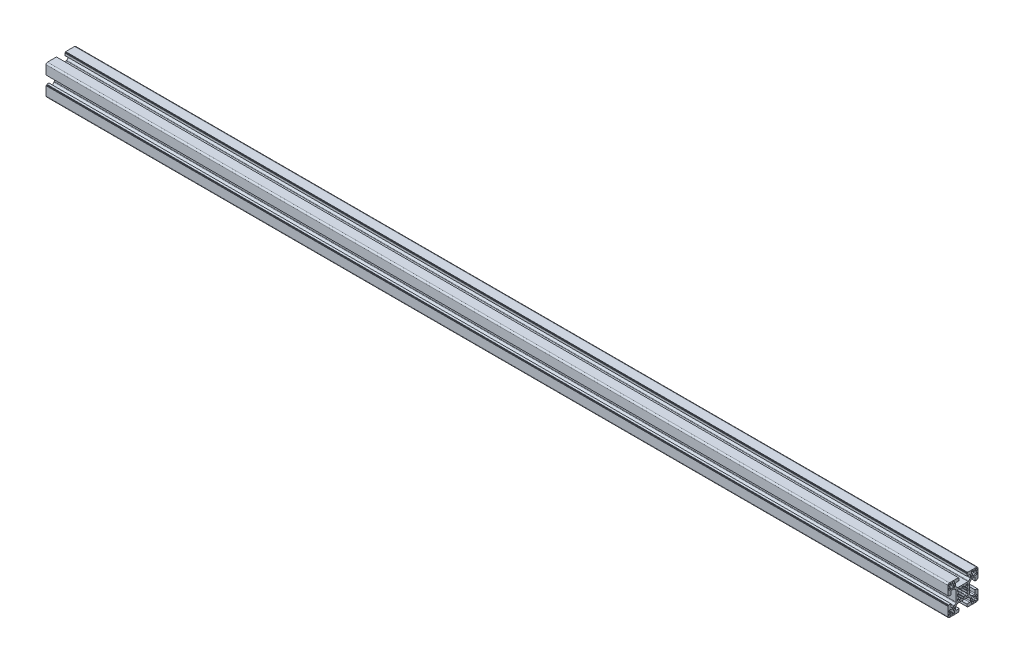
SolidWorks part; units mm, degrees
material "6061 Alloy"
ref_plane "Front Plane" through (0, 0, 0) normal (0, 0, 1) x (1, 0, 0)
ref_plane "Top Plane" through (0, 0, 0) normal (0, 1, 0) x (1, 0, 0)
ref_plane "Right Plane" through (0, 0, 0) normal (1, 0, 0) x (0, 0, -1)
sketch3d "3DSketch1"
  line L12 (-1068.9493, 47.0087, 0) -> (131.0507, 47.0087, 0)
  dimension "D1" = 1200
other " C:\\PROGRAM FILES\\SOLIDWORKS CORP\\SOLIDWORKS\\DATA\\WELDMENT PROFILES\\CUSTOM\\CUSTOM ROHR\\ALUPROFILE 40X40 - IS MISSING(1)"
ref_plane "Plane4" through (-1068.9493, 47.0087, 0) normal (1, 0, 0) x (0, 0, -1)
sketch "Sketch1" plane through (-1068.9493, 47.0087, 0) normal (1, 0, 0) x (0, 0, -1)
  line L0 (-20, 18) -> (-20, 6.1)
  line L1 (-20, 6.1) -> (-19, 6.1)
  line L2 (-19, 6.1) -> (-19, 5.1)
  line L3 (-19, 5.1) -> (-16, 5.1)
  line L4 (-16, 5.1) -> (-16, 9)
  line L5 (-15, 10) -> (-12.182, 10)
  line L6 (-11.4749, 9.7071) -> (-9.2929, 7.5251)
  line L7 (-9, 6.818) -> (-9, -6.818)
  line L8 (-9.2929, -7.5251) -> (-11.4749, -9.7071)
  line L9 (-12.182, -10) -> (-15, -10)
  line L10 (-16, -9) -> (-16, -5.1)
  line L11 (-16, -5.1) -> (-19, -5.1)
  line L12 (-19, -5.1) -> (-19, -6.1)
  line L13 (-19, -6.1) -> (-20, -6.1)
  line L14 (-20, -6.1) -> (-20, -18)
  line L15 (-18, -20) -> (-6.1, -20)
  line L16 (-6.1, -20) -> (-6.1, -19)
  line L17 (-6.1, -19) -> (-5.1, -19)
  line L18 (-5.1, -19) -> (-5.1, -16)
  line L19 (-5.1, -16) -> (-9, -16)
  line L20 (-10, -15) -> (-10, -12.182)
  line L21 (-9.7071, -11.4749) -> (-7.5251, -9.2929)
  line L22 (-6.818, -9) -> (6.818, -9)
  line L23 (7.5251, -9.2929) -> (9.7071, -11.4749)
  line L24 (10, -12.182) -> (10, -15)
  line L25 (9, -16) -> (5.1, -16)
  line L26 (5.1, -16) -> (5.1, -19)
  line L27 (5.1, -19) -> (6.1, -19)
  line L28 (6.1, -19) -> (6.1, -20)
  line L29 (6.1, -20) -> (18, -20)
  line L30 (20, -18) -> (20, -6.1)
  line L31 (20, -6.1) -> (19, -6.1)
  line L32 (19, -6.1) -> (19, -5.1)
  line L33 (19, -5.1) -> (16, -5.1)
  line L34 (16, -5.1) -> (16, -9)
  line L35 (15, -10) -> (12.182, -10)
  line L36 (11.4749, -9.7071) -> (9.2929, -7.5251)
  line L37 (9, -6.818) -> (9, 6.818)
  line L38 (9.2929, 7.5251) -> (11.4749, 9.7071)
  line L39 (12.182, 10) -> (15, 10)
  line L40 (16, 9) -> (16, 5.1)
  line L41 (16, 5.1) -> (19, 5.1)
  line L42 (19, 5.1) -> (19, 6.1)
  line L43 (19, 6.1) -> (20, 6.1)
  line L44 (20, 6.1) -> (20, 18)
  line L45 (18, 20) -> (6.1, 20)
  line L46 (6.1, 20) -> (6.1, 19)
  line L47 (6.1, 19) -> (5.1, 19)
  line L48 (5.1, 19) -> (5.1, 16)
  line L49 (5.1, 16) -> (9, 16)
  line L50 (10, 15) -> (10, 12.182)
  line L51 (9.7071, 11.4749) -> (7.5251, 9.2929)
  line L52 (6.818, 9) -> (-6.818, 9)
  line L53 (-7.5251, 9.2929) -> (-9.7071, 11.4749)
  line L54 (-10, 12.182) -> (-10, 15)
  line L55 (-9, 16) -> (-5.1, 16)
  line L56 (-5.1, 16) -> (-5.1, 19)
  line L57 (-5.1, 19) -> (-6.1, 19)
  line L58 (-6.1, 19) -> (-6.1, 20)
  line L59 (-6.1, 20) -> (-18, 20)
  line L60 (-15.8, 18.5) -> (-15.8, 16.8697)
  line L61 (-15.8, 16.8697) -> (-14.2, 16.8697)
  line L62 (-14.2, 16.8697) -> (-14.2, 18.5)
  line L63 (-14.2, 18.5) -> (-11.5, 18.5)
  line L64 (-11.5, 18.5) -> (-11.5, 15.1697)
  line L65 (-11.5, 15.1697) -> (-12.5, 15.1697)
  line L66 (-12.5, 15.1697) -> (-12.5, 13.5697)
  line L67 (-12.5, 13.5697) -> (-11.5, 13.5697)
  line L68 (-11.5, 13.5697) -> (-11.5, 11.5)
  line L69 (-11.5, 11.5) -> (-14.2, 11.5)
  line L70 (-14.2, 11.5) -> (-14.2, 12.5)
  line L71 (-14.2, 12.5) -> (-15.8, 12.5)
  line L72 (-15.8, 12.5) -> (-15.8, 11.5)
  line L73 (-15.8, 11.5) -> (-18.5, 11.5)
  line L74 (-18.5, 11.5) -> (-18.5, 14.2)
  line L75 (-18.5, 14.2) -> (-17.5, 14.2)
  line L76 (-17.5, 14.2) -> (-17.5, 15.8)
  line L77 (-17.5, 15.8) -> (-18.5, 15.8)
  line L78 (-18.5, 15.8) -> (-18.5, 17.5)
  line L79 (-17.5, 18.5) -> (-15.8, 18.5)
  line L80 (0, 9) -> (0, -9) construction
  line L81 (-9, 0) -> (9, 0) construction
  line L82 (17.5, 18.5) -> (15.8, 18.5)
  line L83 (18.5, 15.8) -> (18.5, 17.5)
  line L84 (17.5, 15.8) -> (18.5, 15.8)
  line L85 (17.5, 14.2) -> (17.5, 15.8)
  line L86 (18.5, 14.2) -> (17.5, 14.2)
  line L87 (18.5, 11.5) -> (18.5, 14.2)
  line L88 (15.8, 11.5) -> (18.5, 11.5)
  line L89 (15.8, 12.5) -> (15.8, 11.5)
  line L90 (14.2, 12.5) -> (15.8, 12.5)
  line L91 (14.2, 11.5) -> (14.2, 12.5)
  line L92 (11.5, 11.5) -> (14.2, 11.5)
  line L93 (11.5, 13.5697) -> (11.5, 11.5)
  line L94 (12.5, 13.5697) -> (11.5, 13.5697)
  line L95 (12.5, 15.1697) -> (12.5, 13.5697)
  line L96 (11.5, 15.1697) -> (12.5, 15.1697)
  line L97 (11.5, 18.5) -> (11.5, 15.1697)
  line L98 (14.2, 18.5) -> (11.5, 18.5)
  line L99 (14.2, 16.8697) -> (14.2, 18.5)
  line L100 (15.8, 16.8697) -> (14.2, 16.8697)
  line L101 (15.8, 18.5) -> (15.8, 16.8697)
  line L102 (15.8, -18.5) -> (15.8, -16.8697)
  line L103 (15.8, -16.8697) -> (14.2, -16.8697)
  line L104 (14.2, -16.8697) -> (14.2, -18.5)
  line L105 (14.2, -18.5) -> (11.5, -18.5)
  line L106 (11.5, -18.5) -> (11.5, -15.1697)
  line L107 (11.5, -15.1697) -> (12.5, -15.1697)
  line L108 (12.5, -15.1697) -> (12.5, -13.5697)
  line L109 (12.5, -13.5697) -> (11.5, -13.5697)
  line L110 (11.5, -13.5697) -> (11.5, -11.5)
  line L111 (11.5, -11.5) -> (14.2, -11.5)
  line L112 (14.2, -11.5) -> (14.2, -12.5)
  line L113 (14.2, -12.5) -> (15.8, -12.5)
  line L114 (15.8, -12.5) -> (15.8, -11.5)
  line L115 (15.8, -11.5) -> (18.5, -11.5)
  line L116 (18.5, -11.5) -> (18.5, -14.2)
  line L117 (18.5, -14.2) -> (17.5, -14.2)
  line L118 (17.5, -14.2) -> (17.5, -15.8)
  line L119 (17.5, -15.8) -> (18.5, -15.8)
  line L120 (18.5, -15.8) -> (18.5, -17.5)
  line L121 (17.5, -18.5) -> (15.8, -18.5)
  line L122 (-17.5, -18.5) -> (-15.8, -18.5)
  line L123 (-18.5, -15.8) -> (-18.5, -17.5)
  line L124 (-17.5, -15.8) -> (-18.5, -15.8)
  line L125 (-17.5, -14.2) -> (-17.5, -15.8)
  line L126 (-18.5, -14.2) -> (-17.5, -14.2)
  line L127 (-18.5, -11.5) -> (-18.5, -14.2)
  line L128 (-15.8, -11.5) -> (-18.5, -11.5)
  line L129 (-15.8, -12.5) -> (-15.8, -11.5)
  line L130 (-14.2, -12.5) -> (-15.8, -12.5)
  line L131 (-14.2, -11.5) -> (-14.2, -12.5)
  line L132 (-11.5, -11.5) -> (-14.2, -11.5)
  line L133 (-11.5, -13.5697) -> (-11.5, -11.5)
  line L134 (-12.5, -13.5697) -> (-11.5, -13.5697)
  line L135 (-12.5, -15.1697) -> (-12.5, -13.5697)
  line L136 (-11.5, -15.1697) -> (-12.5, -15.1697)
  line L137 (-11.5, -18.5) -> (-11.5, -15.1697)
  line L138 (-14.2, -18.5) -> (-11.5, -18.5)
  line L139 (-14.2, -16.8697) -> (-14.2, -18.5)
  line L140 (-15.8, -16.8697) -> (-14.2, -16.8697)
  line L141 (-15.8, -18.5) -> (-15.8, -16.8697)
  line L142 (-7, 4.2) -> (-6.1799, 4.2)
  line L143 (-6.1799, 4.2) -> (-5.1155, 3.1356)
  line L144 (-5.1155, 3.1356) -> (-5.5433, 2.2961)
  line L145 (-5.5433, 2.2961) -> (-5.8344, 1.4)
  line L146 (-5.8344, 1.4) -> (-7, 1.4)
  line L147 (-7, 1.4) -> (-7, -1.4)
  line L148 (-7, -1.4) -> (-5.8344, -1.4)
  line L149 (-5.8344, -1.4) -> (-5.5433, -2.2961)
  line L150 (-5.5433, -2.2961) -> (-5.1155, -3.1356)
  line L151 (-5.1155, -3.1356) -> (-6.1799, -4.2)
  line L152 (-6.1799, -4.2) -> (-7, -4.2)
  line L153 (-7, -4.2) -> (-7, -6)
  line L154 (-6, -7) -> (-4.2, -7)
  line L155 (-4.2, -7) -> (-4.2, -6.1799)
  line L156 (-4.2, -6.1799) -> (-3.1356, -5.1155)
  line L157 (-3.1356, -5.1155) -> (-2.2961, -5.5433)
  line L158 (-2.2961, -5.5433) -> (-1.4, -5.8344)
  line L159 (-1.4, -5.8344) -> (-1.4, -7)
  line L160 (-1.4, -7) -> (1.4, -7)
  line L161 (1.4, -7) -> (1.4, -5.8344)
  line L162 (1.4, -5.8344) -> (2.2961, -5.5433)
  line L163 (2.2961, -5.5433) -> (3.1356, -5.1155)
  line L164 (3.1356, -5.1155) -> (4.2, -6.1799)
  line L165 (4.2, -6.1799) -> (4.2, -7)
  line L166 (4.2, -7) -> (6, -7)
  line L167 (7, -6) -> (7, -4.2)
  line L168 (7, -4.2) -> (6.1799, -4.2)
  line L169 (6.1799, -4.2) -> (5.1155, -3.1356)
  line L170 (5.1155, -3.1356) -> (5.5433, -2.2961)
  line L171 (5.5433, -2.2961) -> (5.8344, -1.4)
  line L172 (5.8344, -1.4) -> (7, -1.4)
  line L173 (7, -1.4) -> (7, 1.4)
  line L174 (7, 1.4) -> (5.8344, 1.4)
  line L175 (5.8344, 1.4) -> (5.5433, 2.2961)
  line L176 (5.5433, 2.2961) -> (5.1155, 3.1356)
  line L177 (5.1155, 3.1356) -> (6.1799, 4.2)
  line L178 (6.1799, 4.2) -> (7, 4.2)
  line L179 (7, 4.2) -> (7, 6)
  line L180 (6, 7) -> (4.2, 7)
  line L181 (4.2, 7) -> (4.2, 6.1799)
  line L182 (4.2, 6.1799) -> (3.1356, 5.1155)
  line L183 (3.1356, 5.1155) -> (2.2961, 5.5433)
  line L184 (2.2961, 5.5433) -> (1.4, 5.8344)
  line L185 (1.4, 5.8344) -> (1.4, 7)
  line L186 (1.4, 7) -> (-1.4, 7)
  line L187 (-1.4, 7) -> (-1.4, 5.8344)
  line L188 (-1.4, 5.8344) -> (-2.2961, 5.5433)
  line L189 (-2.2961, 5.5433) -> (-3.1356, 5.1155)
  line L190 (-3.1356, 5.1155) -> (-4.2, 6.1799)
  line L191 (-4.2, 6.1799) -> (-4.2, 7)
  line L192 (-4.2, 7) -> (-6, 7)
  line L193 (-7, 6) -> (-7, 4.2)
  line L194 (-20, 18) -> (20, 18) construction
  line L195 (18, 20) -> (18, -20) construction
  arc A0 (-16, 9) -> (-15, 10) centre (-15, 9) cw
  arc A1 (-12.182, 10) -> (-11.4749, 9.7071) centre (-12.182, 9) cw
  arc A2 (-9.2929, 7.5251) -> (-9, 6.818) centre (-10, 6.818) cw
  arc A3 (-9, -6.818) -> (-9.2929, -7.5251) centre (-10, -6.818) cw
  arc A4 (-11.4749, -9.7071) -> (-12.182, -10) centre (-12.182, -9) cw
  arc A5 (-15, -10) -> (-16, -9) centre (-15, -9) cw
  arc A6 (-20, -18) -> (-18, -20) centre (-18, -18) ccw
  arc A7 (-9, -16) -> (-10, -15) centre (-9, -15) cw
  arc A8 (-10, -12.182) -> (-9.7071, -11.4749) centre (-9, -12.182) cw
  arc A9 (-7.5251, -9.2929) -> (-6.818, -9) centre (-6.818, -10) cw
  arc A10 (6.818, -9) -> (7.5251, -9.2929) centre (6.818, -10) cw
  arc A11 (9.7071, -11.4749) -> (10, -12.182) centre (9, -12.182) cw
  arc A12 (10, -15) -> (9, -16) centre (9, -15) cw
  arc A13 (18, -20) -> (20, -18) centre (18, -18) ccw
  arc A14 (16, -9) -> (15, -10) centre (15, -9) cw
  arc A15 (12.182, -10) -> (11.4749, -9.7071) centre (12.182, -9) cw
  arc A16 (9.2929, -7.5251) -> (9, -6.818) centre (10, -6.818) cw
  arc A17 (9, 6.818) -> (9.2929, 7.5251) centre (10, 6.818) cw
  arc A18 (11.4749, 9.7071) -> (12.182, 10) centre (12.182, 9) cw
  arc A19 (15, 10) -> (16, 9) centre (15, 9) cw
  arc A20 (20, 18) -> (18, 20) centre (18, 18) ccw
  arc A21 (9, 16) -> (10, 15) centre (9, 15) cw
  arc A22 (10, 12.182) -> (9.7071, 11.4749) centre (9, 12.182) cw
  arc A23 (7.5251, 9.2929) -> (6.818, 9) centre (6.818, 10) cw
  arc A24 (-6.818, 9) -> (-7.5251, 9.2929) centre (-6.818, 10) cw
  arc A25 (-9.7071, 11.4749) -> (-10, 12.182) centre (-9, 12.182) cw
  arc A26 (-10, 15) -> (-9, 16) centre (-9, 15) cw
  arc A27 (-18, 20) -> (-20, 18) centre (-18, 18) ccw
  arc A28 (-18.5, 17.5) -> (-17.5, 18.5) centre (-17.5, 17.5) cw
  arc A29 (18.5, 17.5) -> (17.5, 18.5) centre (17.5, 17.5) ccw
  arc A30 (18.5, -17.5) -> (17.5, -18.5) centre (17.5, -17.5) cw
  arc A31 (-18.5, -17.5) -> (-17.5, -18.5) centre (-17.5, -17.5) ccw
  arc A32 (-7, -6) -> (-6, -7) centre (-6, -6) ccw
  arc A33 (6, -7) -> (7, -6) centre (6, -6) ccw
  arc A34 (7, 6) -> (6, 7) centre (6, 6) ccw
  arc A35 (-6, 7) -> (-7, 6) centre (-6, 6) ccw
  point P268 (0, 0)
  point P269 (0, 0)
  dimension "D1" = 1
  dimension "D2" = 1
  dimension "D3" = 1
  dimension "D4" = 1
  dimension "D5" = 1
  dimension "D6" = 1
  dimension "D7" = 2
  dimension "D8" = 1
  dimension "D9" = 1
  dimension "D10" = 1
  dimension "D11" = 1
  dimension "D12" = 1
  dimension "D13" = 1
  dimension "D14" = 2
  dimension "D15" = 1
  dimension "D16" = 1
  dimension "D17" = 1
  dimension "D18" = 1
  dimension "D19" = 1
  dimension "D20" = 1
  dimension "D21" = 2
  dimension "D22" = 1
  dimension "D23" = 1
  dimension "D24" = 1
  dimension "D25" = 1
  dimension "D26" = 1
  dimension "D27" = 1
  dimension "D28" = 2
  dimension "D29" = 1
  dimension "D30" = 0.5
  dimension "D31" = 1
  dimension "D32" = 1
  dimension "D33" = 1
  dimension "D34" = 1
  dimension "D35" = 1
  dimension "D36" = 1
  dimension "D37" = 2
  dimension "D38" = 2.2
  dimension "D39" = 2
  dimension "D40" = 3.8
  dimension "D41" = 5.5
  dimension "D42" = 5.818
  dimension "D43" = 5.818
  dimension "D44" = 6.5
  dimension "D45" = 6.5251
  dimension "D46" = 6.5251
  dimension "D47" = 8
  dimension "D48" = 8
  dimension "D49" = 8.2929
  dimension "D50" = 8.2929
  dimension "D51" = 10.4749
  dimension "D52" = 10.4749
  dimension "D53" = 11
  dimension "D54" = 11.9
  dimension "D55" = 12.9
  dimension "D56" = 13.8
  dimension "D57" = 16.6
  dimension "D58" = 18
  dimension "D59" = 19.4
  dimension "D60" = 22.2
  dimension "D61" = 23.1
  dimension "D62" = 24.1
  dimension "D63" = 24.818
  dimension "D64" = 11.8201
  dimension "D65" = 11.8201
  dimension "D66" = 25
  dimension "D67" = 11.9
  dimension "D68" = 12.1656
  dimension "D69" = 12.1656
  dimension "D70" = 12.4567
  dimension "D71" = 12.4567
  dimension "D72" = 12.8845
  dimension "D73" = 12.8845
  dimension "D74" = 25.5251
  dimension "D75" = 12.9
  dimension "D76" = 25.5251
  dimension "D77" = 13.8
  dimension "D78" = 14.8644
  dimension "D79" = 14.8644
  dimension "D80" = 15.7039
  dimension "D81" = 15.7039
  dimension "D82" = 16.6
  dimension "D83" = 27.2929
  dimension "D84" = 27.2929
  dimension "D85" = 27.7071
  dimension "D86" = 27.7071
  dimension "D87" = 19.4
  dimension "D88" = 20.2961
  dimension "D89" = 20.2961
  dimension "D90" = 21.1356
  dimension "D91" = 21.1356
  dimension "D92" = 22.2
  dimension "D93" = 29.4749
  dimension "D94" = 23.1
  dimension "D95" = 29.4749
  dimension "D96" = 23.1155
  dimension "D97" = 23.1155
  dimension "D98" = 23.5433
  dimension "D99" = 23.5433
  dimension "D100" = 23.8344
  dimension "D101" = 23.8344
  dimension "D102" = 24.1
  dimension "D103" = 30.182
  dimension "D104" = 24.1799
  dimension "D105" = 24.1799
  dimension "D106" = 34
  dimension "D107" = 37
  dimension "D108" = 38
  dimension "D109" = 25
  dimension "D110" = 0.5
  dimension "D111" = 1
  dimension "D112" = 2
  dimension "D113" = 1
  dimension "D114" = 2
  dimension "D115" = 2.2
  dimension "D116" = 3.8
  dimension "D117" = 5.5
  dimension "D118" = 5.818
  dimension "D119" = 6.5
  dimension "D120" = 8
  dimension "D121" = 8
  dimension "D122" = 11
  dimension "D123" = 11.8201
  dimension "D124" = 11.8201
  dimension "D125" = 11.9
  dimension "D126" = 12.1656
  dimension "D127" = 12.1656
  dimension "D128" = 12.4567
  dimension "D129" = 12.4567
  dimension "D130" = 34
  dimension "D131" = 12.8845
  dimension "D132" = 12.9
  dimension "D133" = 13.8
  dimension "D134" = 14.8644
  dimension "D135" = 37
  dimension "D136" = 18
  dimension "D137" = 38
  dimension "D138" = 19.4
  dimension "D139" = 19.4
  dimension "D140" = 11
  dimension "D141" = 23.1
  dimension "D142" = 23.1155
  dimension "D143" = 23.1155
  dimension "D144" = 24.1
  dimension "D145" = 11.9
  dimension "D146" = 25
  dimension "D147" = 27.2929
  dimension "D148" = 34
  dimension "D149" = 37
  dimension "D150" = 38
  dimension "D151" = 13.5697
  dimension "D152" = 15.1697
  dimension "D153" = 12.9
  dimension "D154" = 16.8697
  dimension "D155" = 13.8
  dimension "D174" = 23.1
  dimension "D182" = 24.1
  dimension "D210" = 34
  dimension "D213" = 37
